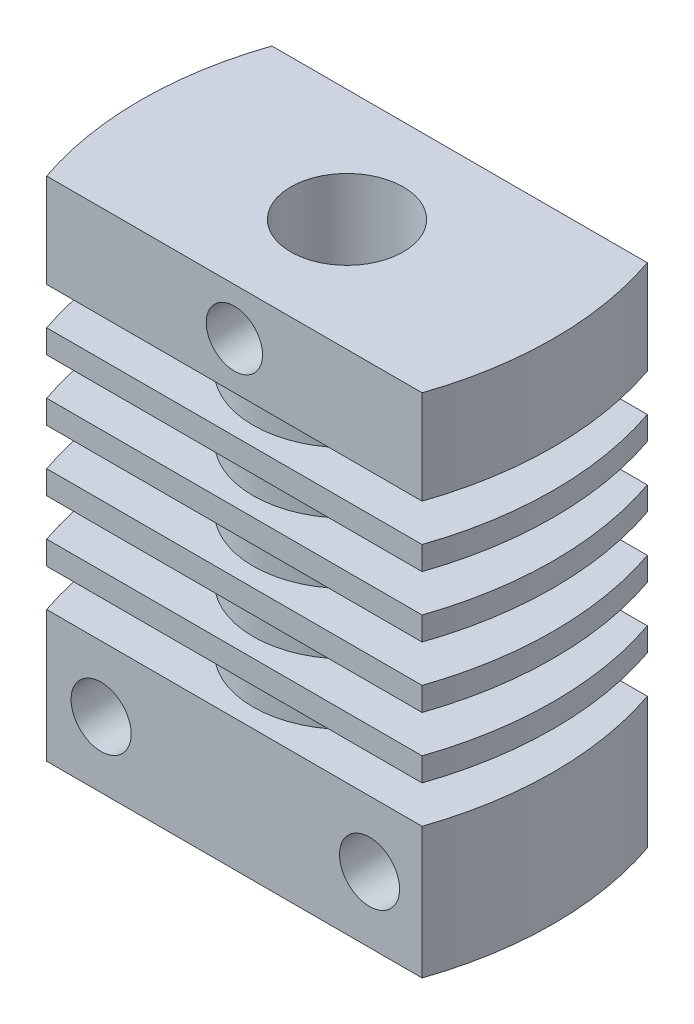
SolidWorks part; units mm, degrees
ref_plane "前视基准面" through (0, 0, 0) normal (0, 0, 1) x (1, 0, 0)
ref_plane "上视基准面" through (0, 0, 0) normal (0, 1, 0) x (1, 0, 0)
ref_plane "右视基准面" through (0, 0, 0) normal (1, 0, 0) x (0, 0, -1)
sketch "草图1" plane through (0, 0, 0) normal (0, 1, 0) x (1, 0, 0)
  line L0 (-7.2644, 3.8391) -> (-8.2644, 3.8391) construction
  line L1 (-7.2644, 3.8391) -> (12.7356, 3.8391)
  line L3 (-7.2644, -8.1609) -> (12.7356, -8.1609)
  line L5 (-7.2644, 3.8391) -> (12.7356, -8.1609) construction
  line L6 (-7.2644, -8.1609) -> (12.7356, 3.8391) construction
  line L7 (-8.2644, 3.8391) -> (-8.2644, -8.1609) construction
  line L8 (-8.2644, -8.1609) -> (-7.2644, -8.1609) construction
  line L9 (12.7356, 3.8391) -> (13.7356, 3.8391) construction
  line L10 (13.7356, 3.8391) -> (13.7356, -8.1609) construction
  line L11 (13.7356, -8.1609) -> (12.7356, -8.1609) construction
  arc A0 (-7.2644, 3.8391) -> (-7.2644, -8.1609) centre (10.2356, -2.1609) ccw
  arc A1 (12.7356, 3.8391) -> (12.7356, -8.1609) centre (-4.7644, -2.1609) cw
  point P4 (2.7356, -2.1609)
  dimension "D1" = 12
  dimension "D2" = 20
  dimension "D3" = 1
  dimension "D4" = 1
extrude "凸台-拉伸1" add sketch "草图1" along normal blind 7
sketch "草图2" plane through (0, 7, 0) normal (0, 1, 0) x (1, 0, 0)
  circle A0 centre (2.7356, -2.1609) radius 5
  dimension "D1" = 10
extrude "凸台-拉伸2" add sketch "草图2" along normal blind 15
ref_plane "基准面1" through (0, 9, 0) normal (0, 1, 0) x (1, 0, 0)
sketch "草图4" plane through (0, 9, 0) normal (0, 1, 0) x (1, 0, 0)
  line L2 (-7.2644, -8.1609) -> (12.7356, -8.1609)
  line L3 (12.7356, 3.8391) -> (-7.2644, 3.8391)
  line L4 (-7.2644, -8.1609) -> (12.7356, -8.1609)
  line L5 (12.7356, 3.8391) -> (-7.2644, 3.8391)
  arc A2 (-7.2644, 3.8391) -> (-7.2644, -8.1609) centre (10.2356, -2.1609) ccw
  arc A3 (12.7356, -8.1609) -> (12.7356, 3.8391) centre (-4.7644, -2.1609) ccw
  arc A4 (-7.2644, 3.8391) -> (-7.2644, -8.1609) centre (10.2356, -2.1609) ccw
  arc A5 (12.7356, -8.1609) -> (12.7356, 3.8391) centre (-4.7644, -2.1609) ccw
  dimension "D1" = 0
extrude "凸台-拉伸3" add sketch "草图4" along normal blind 1.25
pattern_linear "阵列(线性)1" count 4 spacing 3.25 along (0, 1, 0) of "凸台-拉伸3"
sketch "草图6" plane through (0, 22, 0) normal (0, 1, 0) x (1, 0, 0)
  line L2 (12.7356, 3.8391) -> (-7.2644, 3.8391)
  line L3 (-7.2644, -8.1609) -> (12.7356, -8.1609)
  line L4 (12.7356, 3.8391) -> (-7.2644, 3.8391)
  line L5 (-7.2644, -8.1609) -> (12.7356, -8.1609)
  arc A2 (-7.2644, 3.8391) -> (-7.2644, -8.1609) centre (10.2356, -2.1609) ccw
  arc A3 (12.7356, -8.1609) -> (12.7356, 3.8391) centre (-4.7644, -2.1609) ccw
  arc A4 (-7.2644, 3.8391) -> (-7.2644, -8.1609) centre (10.2356, -2.1609) ccw
  arc A5 (12.7356, -8.1609) -> (12.7356, 3.8391) centre (-4.7644, -2.1609) ccw
  dimension "D1" = 0
extrude "凸台-拉伸5" add sketch "草图6" along normal blind 5
sketch "草图8" plane through (0, 0, 8.1609) normal (0, 0, 1) x (1, 0, 0)
  line L0 (-7.2644, 3.5) -> (12.7356, 3.5) construction
  line L1 (-7.2644, 7) -> (-7.2644, 0) construction
  line L2 (12.7356, 7) -> (12.7356, 0) construction
  circle A0 centre (-4.3644, 3.5) radius 1.6
  circle A1 centre (9.9356, 3.5) radius 1.6
  dimension "D1" = 3.2
  dimension "D2" = 3.2
  dimension "D3" = 14.3
  dimension "D4" = 2.8
extrude "切除-拉伸2" cut sketch "草图8" against normal through all
sketch "草图9" plane through (0, 0, 8.1609) normal (0, 0, 1) x (1, 0, 0)
  line L0 (-7.2644, 24.5) -> (12.7356, 24.5) construction
  line L1 (-7.2644, 27) -> (-7.2644, 22) construction
  line L2 (12.7356, 27) -> (12.7356, 22) construction
  circle A0 centre (2.7356, 24.5) radius 1.5
  dimension "D1" = 3
extrude "切除-拉伸3" cut sketch "草图9" against normal blind 5
sketch "草图10" plane through (0, 0, 0) normal (0, -1, 0) x (1, 0, 0)
  line L0 (2.7356, 8.1609) -> (2.7364, -3.8391) construction
  line L1 (-7.2644, 8.1609) -> (12.7356, 8.1609) construction
  line L2 (-9.2636, -3.8391) -> (14.7364, -3.8391) construction
  circle A0 centre (2.736, 2.1609) radius 3
  dimension "D1" = 6
extrude "切除-拉伸4" cut sketch "草图10" against normal through all
